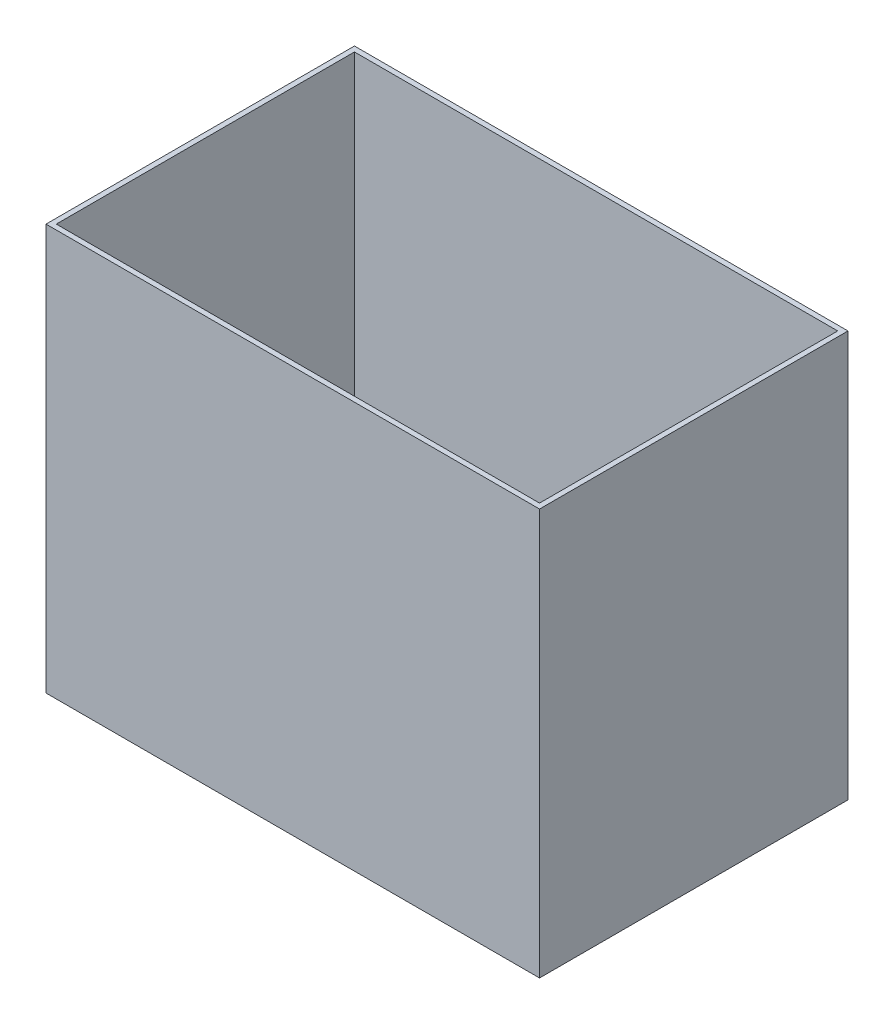
SolidWorks part; units mm, degrees
material "Glass"
ref_plane "Front" through (0, 0, 0) normal (0, 0, 1) x (1, 0, 0)
ref_plane "Top" through (0, 0, 0) normal (0, 1, 0) x (1, 0, 0)
ref_plane "Right" through (0, 0, 0) normal (1, 0, 0) x (0, 0, -1)
sketch "Sketch1" plane through (0, 0, 0) normal (0, 1, 0) x (1, 0, 0)
  line L1 (0, 0) -> (480, 0)
  line L2 (0, 0) -> (0, -300)
  line L3 (0, -300) -> (480, -300)
  line L4 (480, 0) -> (480, -300)
  dimension "D1" = 480
  dimension "D2" = 300
extrude "Boss-Extrude2" add sketch "Sketch1" along normal blind 5
sketch "Sketch2" plane through (0, 5, 0) normal (0, 1, 0) x (1, 0, 0)
  line L0 (5, -5) -> (5, -295)
  line L1 (0, 0) -> (480, 0)
  line L2 (0, 0) -> (0, -300)
  line L3 (0, -300) -> (480, -300)
  line L4 (480, 0) -> (480, -300)
  line L5 (5, -295) -> (475, -295)
  line L6 (475, -5) -> (475, -295)
  line L7 (5, -5) -> (475, -5)
  dimension "D1" = 5
extrude "Boss-Extrude3" add sketch "Sketch2" along normal blind 390
